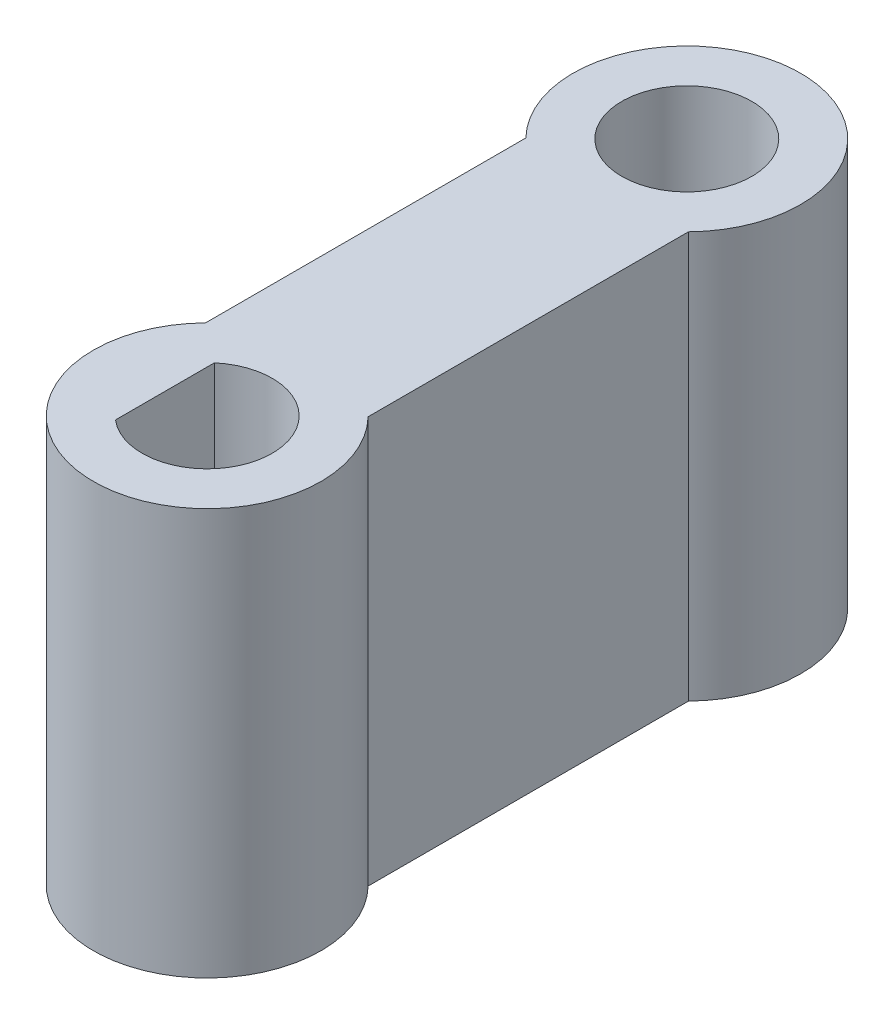
SolidWorks part; units mm, degrees
ref_plane "Front Plane" through (0, 0, 0) normal (0, 0, 1) x (1, 0, 0)
ref_plane "Top Plane" through (0, 0, 0) normal (0, 1, 0) x (1, 0, 0)
ref_plane "Right Plane" through (0, 0, 0) normal (1, 0, 0) x (0, 0, -1)
sketch "Sketch1" plane through (0, 0, 0) normal (0, 1, 0) x (1, 0, 0)
  line L0 (-5, 0) -> (-5, 29.5)
  line L1 (5, 0) -> (5, 29.5)
  arc A0 (-5, 0) -> (5, 0) centre (0, 0) ccw
  arc A1 (5, 29.5) -> (-5, 29.5) centre (0, 29.5) ccw
  circle A2 centre (0, 29.5) radius 2
  circle A3 centre (0, 0) radius 2
  dimension "D1" = 4
  dimension "D2" = 4
  dimension "D4" = 5
  dimension "D3" = 29.5
extrude "Boss-Extrude1" add sketch "Sketch1" along normal blind 25
fillet "Fillet1" [suppressed] radius 1
sketch "Sketch3" plane through (0, 25, 0) normal (0, 1, 0) x (1, 0, 0)
  circle A1 centre (0, 29.5) radius 7
  circle A3 centre (0, 0) radius 7
  circle A4 centre (0, 29.5) radius 2 construction
  circle A5 centre (0, 0) radius 2
  circle A6 centre (0, 0) radius 2
  circle A7 centre (0, 29.5) radius 2
  dimension "D1" = 0
  dimension "D2" = 14
extrude "Boss-Extrude2" add sketch "Sketch3" against normal up to surface (25 mm away) up to face at (0, 0, -14.75)
sketch "Sketch4" plane through (0, 25, 0) normal (0, 1, 0) x (1, 0, 0)
  circle A0 centre (0, 0) radius 5
  dimension "D1" = 10
extrude "Cut-Extrude1" [suppressed] cut sketch "Sketch4" against normal through all
other "Move Face1" face at (0, 25, -27.5) face at (0, 25, 2) parameters "D1"=2
sketch "Sketch5" plane through (0, 25, 0) normal (0, 1, 0) x (1, 0, 0)
  line L0 (-2.6, 3.0397) -> (-2.6, -3.0397)
  circle A0 centre (0, 0) radius 4 construction
  circle A2 centre (0, 0) radius 4
  arc A3 (-2.6, 3.0397) -> (-2.6, -3.0397) centre (0, 0) ccw
  point P4 (-4, 0)
  dimension "D1" = 0
  dimension "D2" = 1.4
extrude "Boss-Extrude3" add sketch "Sketch5" against normal up to surface (25 mm away) up to face at (0, 0, -14.75)
